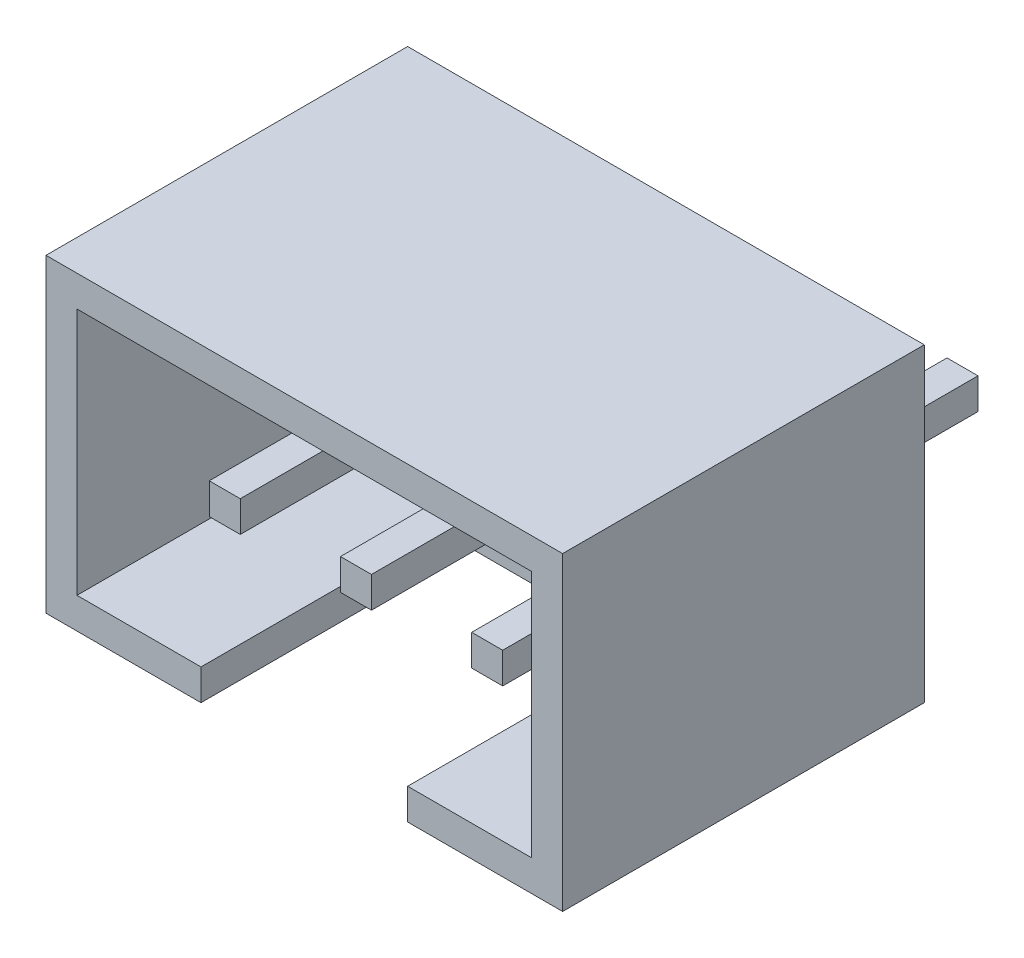
SolidWorks part; units mm, degrees
ref_plane "Front Plane" through (0, 0, 0) normal (0, 0, 1) x (1, 0, 0)
ref_plane "Top Plane" through (0, 0, 0) normal (0, 1, 0) x (1, 0, 0)
ref_plane "Right Plane" through (0, 0, 0) normal (1, 0, 0) x (0, 0, -1)
sketch "Sketch1" plane through (0, 0, 0) normal (0, 0, 1) x (1, 0, 0)
  line L1 (-5, 3) -> (5, 3)
  line L2 (-5, 3) -> (-5, -3)
  line L3 (-5, -3) -> (5, -3)
  line L4 (5, 3) -> (5, -3)
  line L5 (-5, 3) -> (5, -3) construction
  line L6 (-5, -3) -> (5, 3) construction
  point P0 (0, 0)
  dimension "D1" = 10
  dimension "D2" = 6
extrude "Boss-Extrude1" add sketch "Sketch1" along normal blind 1.8
sketch "Sketch2" plane through (0, 0, 1.8) normal (0, 0, 1) x (1, 0, 0)
  line L0 (-2, -3) -> (-2, -2.4)
  line L1 (-5, -3) -> (5, -3) construction
  line L2 (-2, -2.4) -> (-4.4, -2.4)
  line L3 (-4.4, -2.4) -> (-4.4, 2.4)
  line L4 (-4.4, 2.4) -> (4.4, 2.4)
  line L5 (0, 2.4) -> (0, 0) construction
  line L6 (-2, -3) -> (-5, -3)
  line L7 (-5, -3) -> (-5, 3)
  line L8 (-5, 3) -> (5, 3)
  line L9 (5, 3) -> (-5, 3) construction
  line L10 (5, -3) -> (5, 3)
  line L11 (2, -3) -> (5, -3)
  line L12 (2, -3) -> (2, -2.4)
  line L13 (2, -2.4) -> (4.4, -2.4)
  line L14 (4.4, -2.4) -> (4.4, 2.4)
  point P22 (0, 3)
  dimension "D1" = 3
  dimension "D2" = 0.6
  dimension "D3" = 0.6
  dimension "D4" = 0.6
extrude "Boss-Extrude2" add sketch "Sketch2" along normal offset from surface (5.2 mm away) 7 up to face at (0, 0, 0)
sketch "Sketch3" plane through (0, 0, 1.8) normal (0, 0, 1) x (1, 0, 0)
  line L0 (-2, -3) -> (2, -3) construction
  line L1 (-2.84, -0.2) -> (-2.24, -0.2)
  line L2 (-2.84, -0.2) -> (-2.84, -0.8)
  line L3 (-2.84, -0.8) -> (-2.24, -0.8)
  line L4 (-2.24, -0.2) -> (-2.24, -0.8)
  point P4 (-2.84, -0.5)
  point P7 (-2.54, -0.8)
  dimension "D1" = 0.6
  dimension "D2" = 2.5
  dimension "D3" = 2.54
extrude "Boss-Extrude3" add sketch "Sketch3" along normal offset from surface 6 and the other way blind 5 up to face at (0, 0, 0)
pattern_linear "LPattern1" count 3 spacing 2.54 along (1, 0, 0) of "Boss-Extrude3"
